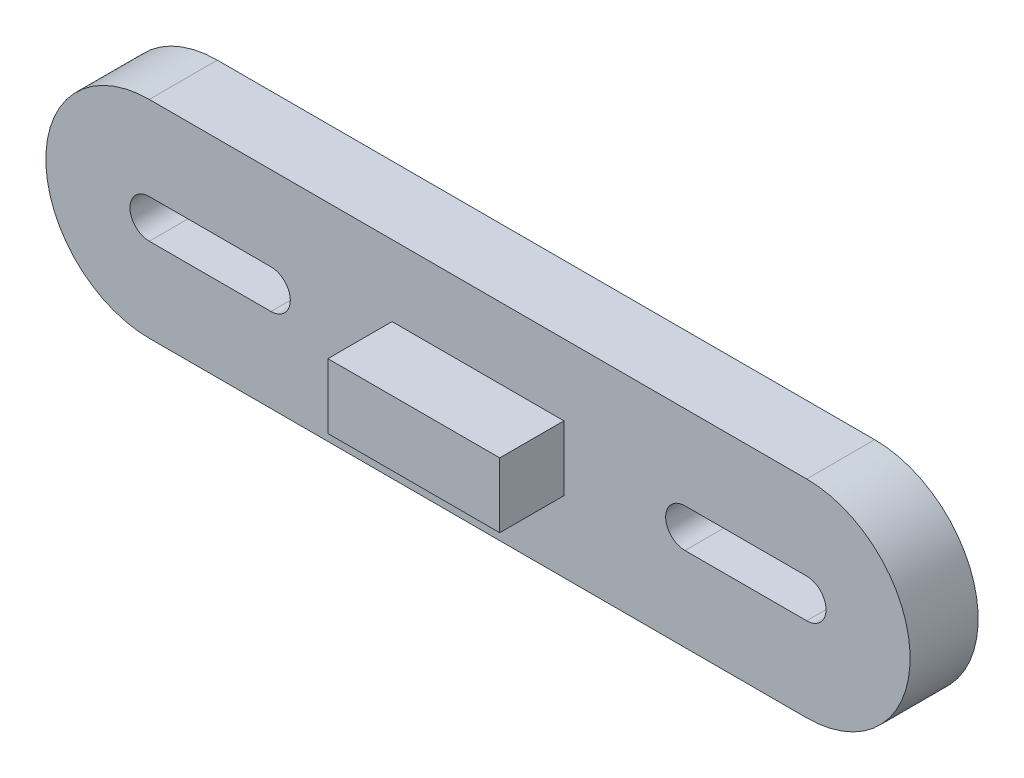
SolidWorks part; units mm, degrees
ref_plane "Front Plane" through (0, 0, 0) normal (0, 0, 1) x (1, 0, 0)
ref_plane "Top Plane" through (0, 0, 0) normal (0, 1, 0) x (1, 0, 0)
ref_plane "Right Plane" through (0, 0, 0) normal (1, 0, 0) x (0, 0, -1)
sketch "Sketch3" plane through (0, 0, 0) normal (0, 0, 1) x (1, 0, 0)
  line L0 (-14.345, 0) -> (14.345, 0) construction
  line L1 (-14.345, 4.5144) -> (14.345, 4.5144)
  line L2 (-14.345, -4.5144) -> (14.345, -4.5144)
  line L3 (-14.345, 0) -> (-9.035, 0) construction
  line L4 (-14.345, 0.8444) -> (-9.035, 0.8444)
  line L5 (-14.345, -0.8444) -> (-9.035, -0.8444)
  line L6 (14.345, 0) -> (9.035, 0) construction
  line L7 (14.345, -0.8444) -> (9.035, -0.8444)
  line L8 (14.345, 0.8444) -> (9.035, 0.8444)
  arc A0 (-14.345, 4.5144) -> (-14.345, -4.5144) centre (-14.345, 0) ccw
  arc A1 (14.345, -4.5144) -> (14.345, 4.5144) centre (14.345, 0) ccw
  arc A2 (-14.345, 0.8444) -> (-14.345, -0.8444) centre (-14.345, 0) ccw
  arc A3 (-9.035, -0.8444) -> (-9.035, 0.8444) centre (-9.035, 0) ccw
  arc A4 (14.345, -0.8444) -> (14.345, 0.8444) centre (14.345, 0) ccw
  arc A5 (9.035, 0.8444) -> (9.035, -0.8444) centre (9.035, 0) ccw
  point P3 (0, 0)
  point P10 (-11.69, 0)
  point P17 (11.69, 0)
  point P22 (14.345, -4.5144)
  point P23 (0, 0)
  dimension "D2" = 4.5144
  dimension "D3" = 3.67
  dimension "D5" = 3.67
  dimension "D1" = 28.69
  dimension "D4" = 5.31
  dimension "D6" = 5.31
  dimension "D7" = 0
  dimension "D8" = 0
extrude "Boss-Extrude2" add sketch "Sketch3" along normal blind 2.97
sketch "Sketch5" plane through (0, 0, 2.97) normal (0, 0, 1) x (1, 0, 0)
  line L1 (-3.75, 1.415) -> (3.75, 1.415)
  line L2 (-3.75, 1.415) -> (-3.75, -1.415)
  line L3 (-3.75, -1.415) -> (3.75, -1.415)
  line L4 (3.75, 1.415) -> (3.75, -1.415)
  line L5 (-3.75, 1.415) -> (3.75, -1.415) construction
  line L6 (-3.75, -1.415) -> (3.75, 1.415) construction
  point P0 (0, 0)
  point P5 (0, 0)
  dimension "D1" = 7.5
  dimension "D2" = 2.83
extrude "Boss-Extrude3" add sketch "Sketch5" along normal blind 2.8
